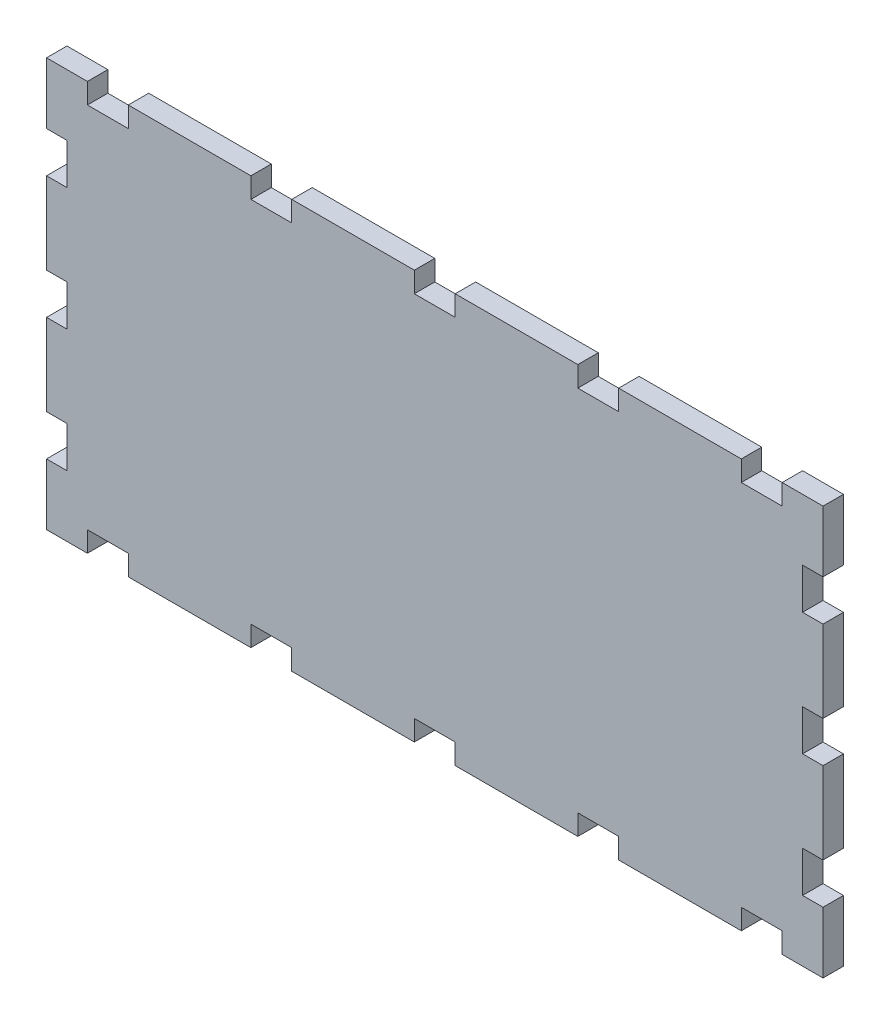
SolidWorks part; units mm, degrees
ref_plane "Ön Düzlem" through (0, 0, 0) normal (0, 0, 1) x (1, 0, 0)
ref_plane "Üst Düzlem" through (0, 0, 0) normal (0, 1, 0) x (1, 0, 0)
ref_plane "Sağ Düzlem" through (0, 0, 0) normal (1, 0, 0) x (0, 0, -1)
sketch "Sketch1" plane through (0, 0, 0) normal (0, 0, 1) x (1, 0, 0)
  line L0 (-85, 50) -> (-85, 45)
  line L1 (-95, -50) -> (95, -50)
  line L2 (-95, -50) -> (-95, 50)
  line L3 (-95, 50) -> (95, 50)
  line L4 (95, -50) -> (95, 50)
  line L5 (-95, -50) -> (95, 50) construction
  line L6 (-95, 50) -> (95, -50) construction
  line L7 (-85, 45) -> (-75, 45)
  line L8 (-75, 45) -> (-75, 50)
  line L9 (-85, -50) -> (-85, -45)
  line L10 (-85, -45) -> (-75, -45)
  line L11 (-75, -45) -> (-75, -50)
  line L12 (-95, 35) -> (-90, 35)
  line L13 (-90, 35) -> (-90, 25)
  line L14 (-90, 25) -> (-95, 25)
  line L15 (0, 50) -> (0, -50) construction
  line L16 (95, 35) -> (90, 35)
  line L17 (90, 35) -> (90, 25)
  line L18 (90, 25) -> (95, 25)
  line L19 (-45, 50) -> (-45, 45)
  line L20 (-45, 45) -> (-35, 45)
  line L21 (-35, 45) -> (-35, 50)
  line L22 (-45, -50) -> (-45, -45)
  line L23 (-45, -45) -> (-35, -45)
  line L24 (-35, -45) -> (-35, -50)
  line L25 (-5, 50) -> (-5, 45)
  line L26 (-5, 45) -> (5, 45)
  line L27 (5, 45) -> (5, 50)
  line L28 (-5, -50) -> (-5, -45)
  line L29 (-5, -45) -> (5, -45)
  line L30 (5, -45) -> (5, -50)
  line L31 (35, 50) -> (35, 45)
  line L32 (35, 45) -> (45, 45)
  line L33 (45, 45) -> (45, 50)
  line L34 (35, -50) -> (35, -45)
  line L35 (35, -45) -> (45, -45)
  line L36 (45, -45) -> (45, -50)
  line L37 (75, 50) -> (75, 45)
  line L38 (75, 45) -> (85, 45)
  line L39 (85, 45) -> (85, 50)
  line L40 (75, -50) -> (75, -45)
  line L41 (75, -45) -> (85, -45)
  line L42 (85, -45) -> (85, -50)
  line L43 (-95, 5) -> (-90, 5)
  line L44 (-90, 5) -> (-90, -5)
  line L45 (-90, -5) -> (-95, -5)
  line L46 (95, 5) -> (90, 5)
  line L47 (90, 5) -> (90, -5)
  line L48 (90, -5) -> (95, -5)
  line L49 (115, -50) -> (115, -45) [skipped]
  line L50 (115, -45) -> (125, -45) [skipped]
  line L51 (125, -45) -> (125, -50) [skipped]
  line L52 (115, 45) -> (125, 45) [skipped]
  line L53 (125, 45) -> (125, 50) [skipped]
  line L54 (115, 50) -> (115, 45) [skipped]
  line L55 (-95, -25) -> (-90, -25)
  line L56 (-90, -25) -> (-90, -35)
  line L57 (-90, -35) -> (-95, -35)
  line L58 (95, -25) -> (90, -25)
  line L59 (90, -25) -> (90, -35)
  line L60 (90, -35) -> (95, -35)
  point P0 (0, 0)
  dimension "D1" = 190
  dimension "D2" = 100
  dimension "D3" = 5
  dimension "D4" = 10
  dimension "D5" = 10
  dimension "D6" = 15
  dimension "D7" = 5
  dimension "D8" = 10
  dimension "D10" = 30
  dimension "D12" = 20
  dimension "D9" = 6
  dimension "D11" = 3
extrude "Boss-Extrude1" add sketch "Sketch1" along normal blind 5 contours L60 L59 L58 L4 L48 L47 L46 L18 L17 L16 L3 L39 L38 L37 L33 L32 L31 L27 L26 L25 L21 L20 L19 L8 L7 L0 L2 L12 L13 L14 L43 L44 L45 L55 L56 L57 L1 L9 L10 L11
